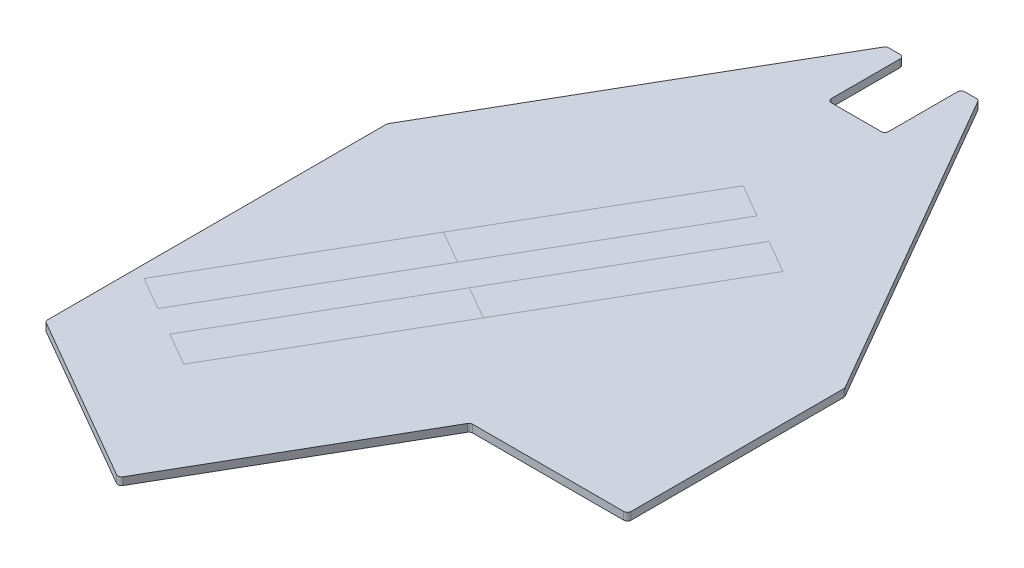
SolidWorks part; units mm, degrees
material "1.0116 (S235J2G3)"
ref_plane "Front Plane" through (0, 0, 0) normal (0, 0, 1) x (1, 0, 0)
ref_plane "Top Plane" through (0, 0, 0) normal (0, 1, 0) x (1, 0, 0)
ref_plane "Right Plane" through (0, 0, 0) normal (1, 0, 0) x (0, 0, -1)
sketch "Sketch1" plane through (0, 0, 0) normal (0, 1, 0) x (1, 0, 0)
  line L0 (0, 0) -> (0, 1800) construction
  line L1 (590, 0) -> (194.4486, 0)
  line L2 (-600, 0) -> (-600, 567.3205)
  line L3 (-598.6603, 572.3205) -> (-123.686, 1395)
  line L4 (-115.0258, 1400) -> (-85, 1400)
  line L5 (-75, 1390) -> (-75, 1210)
  line L6 (-65, 1200) -> (65, 1200)
  line L7 (75, 1390) -> (75, 1210)
  line L8 (115.0258, 1400) -> (85, 1400)
  line L9 (598.6603, 572.3205) -> (123.686, 1395)
  line L10 (600, 10) -> (600, 567.3205)
  line L13 (-144.675, -577.3794) -> (185.7884, -5)
  line L14 (-158.3353, -581.0397) -> (-595, -328.9312)
  line L15 (-600, -320.2709) -> (-600, 0)
  arc A0 (-600, 567.3205) -> (-598.6603, 572.3205) centre (-590, 567.3205) cw
  arc A1 (-595, -328.9312) -> (-600, -320.2709) centre (-590, -320.2709) cw
  arc A2 (-158.3353, -581.0397) -> (-144.675, -577.3794) centre (-153.3353, -572.3794) ccw
  arc A3 (-123.686, 1395) -> (-115.0258, 1400) centre (-115.0258, 1390) cw
  arc A4 (185.7884, -5) -> (194.4486, 0) centre (194.4486, -10) cw
  arc A5 (600, 10) -> (590, 0) centre (590, 10) cw
  arc A6 (598.6603, 572.3205) -> (600, 567.3205) centre (590, 567.3205) cw
  arc A7 (115.0258, 1400) -> (123.686, 1395) centre (115.0258, 1390) cw
  arc A8 (75, 1210) -> (65, 1200) centre (65, 1210) cw
  arc A9 (-75, 1210) -> (-65, 1200) centre (-65, 1210) ccw
  arc A10 (75, 1390) -> (85, 1400) centre (85, 1390) cw
  arc A11 (-85, 1400) -> (-75, 1390) centre (-85, 1390) cw
  point P3 (-100.0129, 1400)
  point P11 (0, 1200)
  point P20 (-600, 570)
  point P23 (-600, -326.0445)
  point P26 (-149.675, -586.0397)
  point P29 (-120.7993, 1400)
  point P32 (188.6751, 0)
  point P35 (600, 0)
  point P38 (600, 570)
  point P41 (120.7993, 1400)
  point P44 (75, 1200)
  point P47 (-75, 1200)
  point P50 (75, 1400)
  point P53 (-75, 1400)
  dimension "D13" = 10
  dimension "D14" = 10
  dimension "D15" = 10
  dimension "D1" = 1800
  dimension "D2" = 600
  dimension "D3" = 570
  dimension "D4" = 1400
  dimension "D5" = 75
  dimension "D6" = 60
  dimension "D7" = 200
  dimension "D8" = 90
  dimension "D9" = 326.0445
  dimension "D10" = 120
  dimension "D11" = 411.3249
  dimension "D12" = 450.325
extrude "Boss-Extrude2" add sketch "Sketch1" along normal blind 20
sketch "Sketch2" plane through (0, 0, 0) normal (0, -1, 0) x (-1, 0, 0)
  line L0 (-600, 34.34) -> (600, 34.34)
  line L1 (-600, 10) -> (-600, 567.3205) construction
  line L2 (600, 0) -> (600, 567.3205) construction
  line L3 (600, 34.34) -> (600, 94.34)
  line L4 (600, 94.34) -> (-600, 94.34)
  line L5 (-600, 94.34) -> (-600, 34.34)
  line L6 (-590, 0) -> (-194.4486, 0) construction
  line L7 (-75, 1366.1467) -> (-600, 456.82)
  line L8 (-75, 1390) -> (-75, 1210) construction
  line L9 (-600, 456.82) -> (-600, 336.82)
  line L10 (-600, 336.82) -> (-75, 1246.1467)
  line L11 (-75, 1246.1467) -> (-75, 1366.1467)
  line L12 (-598.6603, 572.3205) -> (-123.686, 1395) construction
  line L13 (0, -747.4199) -> (0, 2106.0652) construction
  line L14 (600, 336.82) -> (75, 1246.1467)
  line L15 (600, 456.82) -> (600, 336.82)
  line L16 (75, 1366.1467) -> (600, 456.82)
  line L17 (75, 1246.1467) -> (75, 1366.1467)
  dimension "D1" = 94.34
  dimension "D2" = 34.34
  dimension "D3" = 60
  dimension "D4" = 56.59
split line "Split Line1"
sketch "Sketch3" plane through (0, 20, 0) normal (0, 1, 0) x (1, 0, 0)
  line L0 (-320.8032, -242.4423) -> (254.1968, 753.4869)
  line L1 (254.1968, 753.4869) -> (167.5943, 803.4869)
  line L2 (167.5943, 803.4869) -> (-407.4057, -192.4423)
  line L3 (-407.4057, -192.4423) -> (-320.8032, -242.4423)
  line L4 (-280.1204, 398.0223) -> (-193.5179, 348.0223)
  line L5 (-481.0179, -149.9423) -> (93.9821, 845.9869)
  line L6 (93.9821, 845.9869) -> (7.3796, 895.9869)
  line L7 (7.3796, 895.9869) -> (-567.6204, -99.9423)
  line L8 (-567.6204, -99.9423) -> (-481.0179, -149.9423)
  line L9 (-119.9057, 305.5223) -> (-33.3032, 255.5223)
  line L10 (-598.6603, 572.3205) -> (-123.686, 1395) construction
  line L11 (-144.675, -577.3794) -> (185.7884, -5) construction
  line L12 (-158.3353, -581.0397) -> (-595, -328.9312) construction
  dimension "D1" = 100
  dimension "D2" = 1150
  dimension "D3" = 100
  dimension "D4" = 85
  dimension "D5" = 320
  dimension "D6" = 212
  dimension "D7" = 212
  dimension "D8" = 1150
split line "Split Line2"
